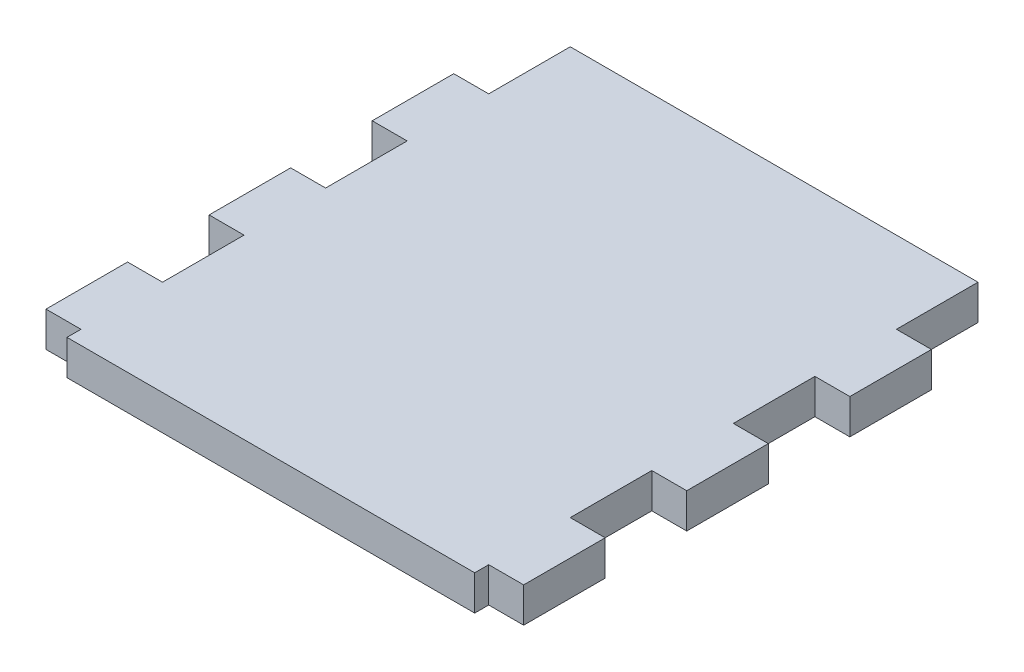
SolidWorks part; units mm, degrees
ref_plane "Front Plane" through (0, 0, 0) normal (0, 0, 1) x (1, 0, 0)
ref_plane "Top Plane" through (0, 0, 0) normal (0, 1, 0) x (1, 0, 0)
ref_plane "Right Plane" through (0, 0, 0) normal (1, 0, 0) x (0, 0, -1)
sketch "Sketch1" plane through (0, 0, 0) normal (0, 1, 0) x (1, 0, 0)
  line L0 (17.5, 42) -> (17.5, 0) construction
  line L1 (0, 0) -> (35, 0)
  line L2 (0, 0) -> (0, 42)
  line L3 (0, 42) -> (35, 42)
  line L4 (35, 0) -> (35, 42)
  line L5 (0, 0) -> (35, 0)
  line L6 (0, 0) -> (0, -1.2)
  line L7 (0, -1.2) -> (35, -1.2)
  line L8 (35, 0) -> (35, -1.2)
  line L9 (35, 35) -> (38, 35)
  line L10 (35, 35) -> (35, 28)
  line L11 (35, 28) -> (38, 28)
  line L12 (38, 35) -> (38, 28)
  line L13 (35, 21) -> (35, 14)
  line L14 (35, 21) -> (38, 21)
  line L15 (38, 21) -> (38, 14)
  line L16 (35, 14) -> (38, 14)
  line L17 (35, 7) -> (35, 0)
  line L18 (35, 7) -> (38, 7)
  line L19 (38, 7) -> (38, 0)
  line L20 (35, 0) -> (38, 0)
  line L21 (0, 7) -> (-3, 7)
  line L22 (-3, 7) -> (-3, 0)
  line L23 (0, 0) -> (-3, 0)
  line L24 (0, 7) -> (0, 0)
  line L25 (0, 21) -> (-3, 21)
  line L26 (-3, 21) -> (-3, 14)
  line L27 (0, 14) -> (-3, 14)
  line L28 (0, 21) -> (0, 14)
  line L29 (0, 28) -> (-3, 28)
  line L30 (-3, 35) -> (-3, 28)
  line L31 (0, 35) -> (-3, 35)
  line L32 (0, 35) -> (0, 28)
  dimension "D1" = 35
  dimension "D2" = 42
  dimension "D3" = 1.2
  dimension "D4" = 7
  dimension "D5" = 7
  dimension "D6" = 3
  dimension "D7" = 3
extrude "Boss-Extrude1" add sketch "Sketch1" along normal blind 3 contours L3 L0 L5 L4 | L12 L9 L4 L11 | L4 L16 L15 L14 | L4 L20 L19 L18 | L0 L3 L2 L1 | L8 L5 L1 L6 L7 | L23 L2 L21 L22 | L27 L2 L25 L26 | L2 L31 L30 L29
